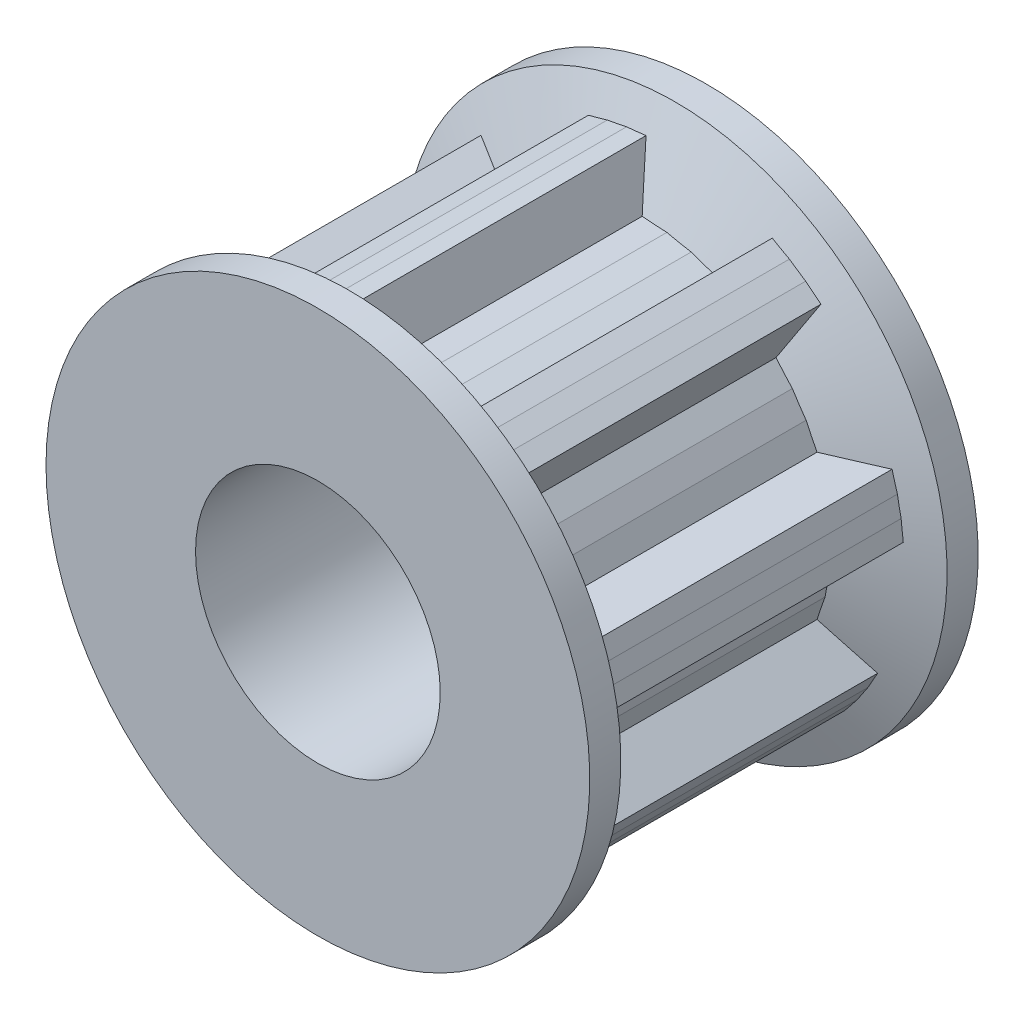
SolidWorks part; units mm, degrees
material "Green ABS"
ref_plane "Front Plane" through (0, 0, 0) normal (0, 0, 1) x (1, 0, 0)
ref_plane "Top Plane" through (0, 0, 0) normal (0, 1, 0) x (1, 0, 0)
ref_plane "Right Plane" through (0, 0, 0) normal (1, 0, 0) x (0, 0, -1)
sketch "Sketch2" plane through (0, 0, 0) normal (0, 0, 1) x (1, 0, 0)
  line L2 (4.8737, 0) -> (4.832, -0.6361)
  line L3 (4.832, -0.6361) -> (4.7076, -1.2614)
  line L7 (4.7076, -1.2614) -> (4.5027, -1.8651)
  line L18 (5.529, -2.8172) -> (5.2815, -3.2577)
  line L20 (4.5027, -1.8651) -> (5.529, -2.8172)
  line L25 (5.2815, -3.2577) -> (4.999, -3.6766)
  line L27 (4.6833, -4.0711) -> (3.4462, -3.4462)
  line L29 (4.999, -3.6766) -> (4.6833, -4.0711)
  line L30 (3.4462, -3.4462) -> (2.9669, -3.8666)
  line L34 (2.9669, -3.8666) -> (2.4369, -4.2208)
  line L37 (2.4369, -4.2208) -> (1.8651, -4.5027)
  line L43 (0, -4.8737) -> (-0.6361, -4.832)
  line L46 (-0.6361, -4.832) -> (-1.2614, -4.7076)
  line L49 (-1.2614, -4.7076) -> (-1.8651, -4.5027)
  line L56 (-3.4462, -3.4462) -> (-3.8666, -2.9669)
  line L57 (-3.8666, -2.9669) -> (-4.2208, -2.4369)
  line L61 (-4.2208, -2.4369) -> (-4.5027, -1.8651)
  line L68 (-4.8737, 0) -> (-4.832, 0.6361)
  line L69 (-4.832, 0.6361) -> (-4.7076, 1.2614)
  line L73 (-4.7076, 1.2614) -> (-4.5027, 1.8651)
  line L84 (1.9176, -5.9017) -> (1.4311, -6.0381)
  line L86 (1.8651, -4.5027) -> (1.9176, -5.9017)
  line L91 (1.4311, -6.0381) -> (0.9351, -6.1345)
  line L93 (0.4329, -6.1903) -> (0, -4.8737)
  line L95 (0.9351, -6.1345) -> (0.4329, -6.1903)
  line L96 (-2.8172, -5.529) -> (-3.2577, -5.2815)
  line L98 (-1.8651, -4.5027) -> (-2.8172, -5.529)
  line L100 (-3.2577, -5.2815) -> (-3.6766, -4.999)
  line L103 (-3.6766, -4.999) -> (-4.0711, -4.6833)
  line L104 (-4.0711, -4.6833) -> (-3.4462, -3.4462)
  line L108 (-5.9017, -1.9176) -> (-6.0381, -1.4311)
  line L110 (-4.5027, -1.8651) -> (-5.9017, -1.9176)
  line L115 (-6.0381, -1.4311) -> (-6.1345, -0.9351)
  line L117 (-6.1903, -0.4329) -> (-4.8737, 0)
  line L119 (-6.1345, -0.9351) -> (-6.1903, -0.4329)
  line L120 (-5.529, 2.8172) -> (-5.2815, 3.2577)
  line L122 (-4.5027, 1.8651) -> (-5.529, 2.8172)
  line L127 (-5.2815, 3.2577) -> (-4.999, 3.6766)
  line L129 (-4.6833, 4.0711) -> (-3.4462, 3.4462)
  line L131 (-4.999, 3.6766) -> (-4.6833, 4.0711)
  line L132 (-3.4462, 3.4462) -> (-2.9669, 3.8666)
  line L136 (-2.9669, 3.8666) -> (-2.4369, 4.2208)
  line L139 (-2.4369, 4.2208) -> (-1.8651, 4.5027)
  line L145 (0, 4.8737) -> (0.6361, 4.832)
  line L148 (0.6361, 4.832) -> (1.2614, 4.7076)
  line L151 (1.2614, 4.7076) -> (1.8651, 4.5027)
  line L158 (3.4462, 3.4462) -> (3.8666, 2.9669)
  line L159 (3.8666, 2.9669) -> (4.2208, 2.4369)
  line L163 (4.2208, 2.4369) -> (4.5027, 1.8651)
  line L171 (-1.9176, 5.9017) -> (-1.4311, 6.0381)
  line L173 (-1.8651, 4.5027) -> (-1.9176, 5.9017)
  line L178 (-1.4311, 6.0381) -> (-0.9351, 6.1345)
  line L180 (-0.4329, 6.1903) -> (0, 4.8737)
  line L182 (-0.9351, 6.1345) -> (-0.4329, 6.1903)
  line L183 (2.8172, 5.529) -> (3.2577, 5.2815)
  line L185 (1.8651, 4.5027) -> (2.8172, 5.529)
  line L187 (3.2577, 5.2815) -> (3.6766, 4.999)
  line L190 (3.6766, 4.999) -> (4.0711, 4.6833)
  line L191 (4.0711, 4.6833) -> (3.4462, 3.4462)
  line L195 (5.9017, 1.9176) -> (6.0381, 1.4311)
  line L197 (4.5027, 1.8651) -> (5.9017, 1.9176)
  line L199 (6.0381, 1.4311) -> (6.1345, 0.9351)
  line L202 (6.1345, 0.9351) -> (6.1903, 0.4329)
  line L203 (6.1903, 0.4329) -> (4.8737, 0)
  circle A0 centre (0, 0) radius 3.15
  dimension "D1" = 6.3
  dimension "D2" = 4.8737
  dimension "D3" = 6.2054
  dimension "D4" = 1.5125
  dimension "D5" = 1.9016
extrude "Boss-Extrude1" add sketch "Sketch2" along normal blind 10
sketch "Sketch3" plane through (0, 0, 0) normal (0, 1, 0) x (1, 0, 0)
  line L0 (-4, 0) -> (-7, 0)
  line L1 (-7, 0) -> (-7, -0.8)
  line L2 (-7, -0.8) -> (-4, -2)
  line L4 (-4, -2) -> (-4, 0)
  line L6 (0, 0) -> (0, -3.0599) construction
  line L7 (0, -10) -> (0, 0) construction
  dimension "D1" = 4
  dimension "D2" = 7
  dimension "D3" = 0.8
  dimension "D4" = 2
revolve "Revolve1" add sketch "Sketch3" angle 360 about L6
ref_plane "Plane1" through (0, 0, 5) normal (0, 0, 1) x (1, 0, 0)
mirror "Mirror1" about plane through (0, 0, 5) normal (0, 0, 1) of "Revolve1"
